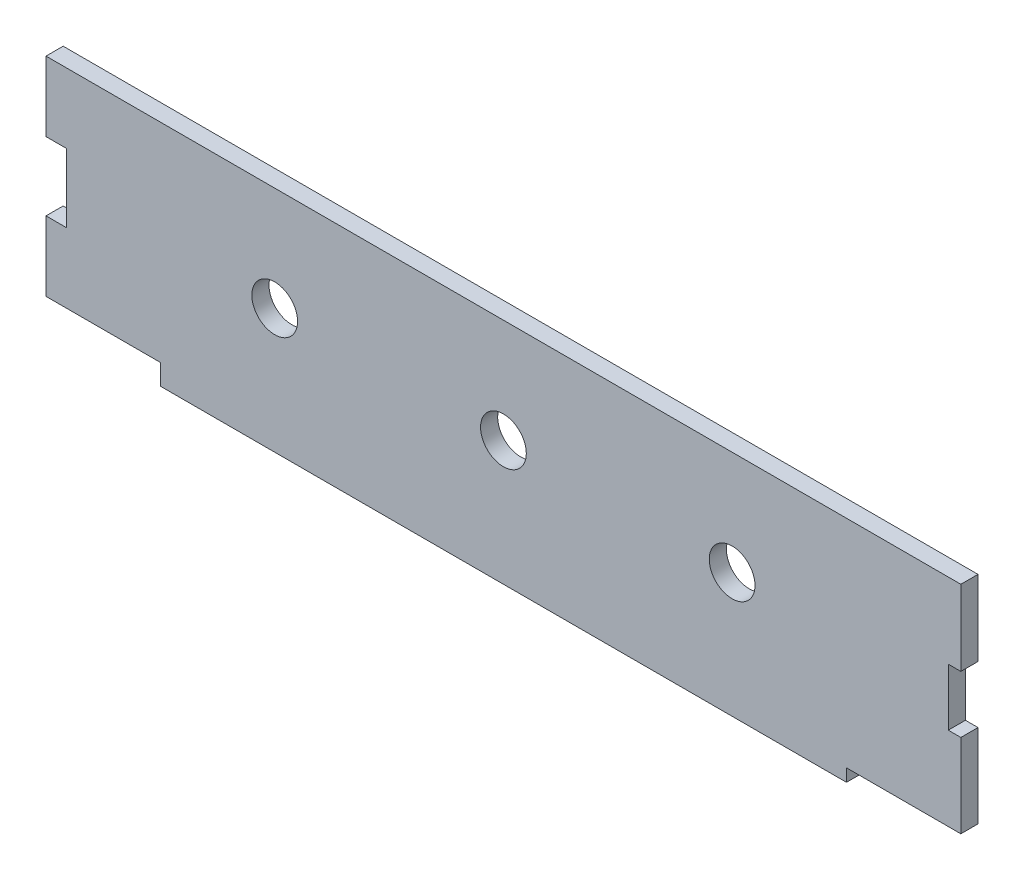
SolidWorks part; units mm, degrees
ref_plane "Alzado" through (0, 0, 0) normal (0, 0, 1) x (1, 0, 0)
ref_plane "Planta" through (0, 0, 0) normal (0, 1, 0) x (1, 0, 0)
ref_plane "Vista lateral" through (0, 0, 0) normal (1, 0, 0) x (0, 0, -1)
sketch "Croquis1" plane through (0, 0, 0) normal (0, 0, 1) x (1, 0, 0)
  line L0 (-40, 9.1) -> (40, 9.1)
  line L1 (40, 9.1) -> (40, 2.5)
  line L2 (40, 2.5) -> (38.9, 2.5)
  line L3 (38.9, 2.5) -> (38.9, -2.5)
  line L4 (38.9, -2.5) -> (40, -2.5)
  line L5 (40, -2.5) -> (40, -9.8)
  line L6 (40, -9.8) -> (30, -9.8)
  line L7 (30, -9.8) -> (30, -10.9)
  line L8 (30, -10.9) -> (-30, -10.9)
  line L9 (-30, -10.9) -> (-30, -9.1)
  line L10 (-30, -9.1) -> (-40, -9.1)
  line L11 (-40, -9.1) -> (-40, -3)
  line L12 (-40, -3) -> (-38.2, -3)
  line L13 (-38.2, -3) -> (-38.2, 3)
  line L14 (-38.2, 3) -> (-40, 3)
  line L15 (-40, 3) -> (-40, 9.1)
  line L16 (38.9, 0) -> (-38.2, 0) construction
  circle A0 centre (20, 0) radius 2
  circle A1 centre (0, 0) radius 2
  circle A2 centre (-20, 0) radius 2
  point P16 (-38.2, 0)
  point P18 (38.9, 0)
  point P19 (0, 9.1)
  dimension "D9" = 4
  dimension "D10" = 20
  dimension "D11" = 20
  dimension "D12" = 20
  dimension "D1" = 80
  dimension "D2" = 10
  dimension "D3" = 10
  dimension "D4" = 20
  dimension "D5" = 6
  dimension "D6" = 5
  dimension "D7" = 1.8
  dimension "D8" = 1.1
extrude "Saliente-Extruir1" add sketch "Croquis1" along normal blind 1.5
